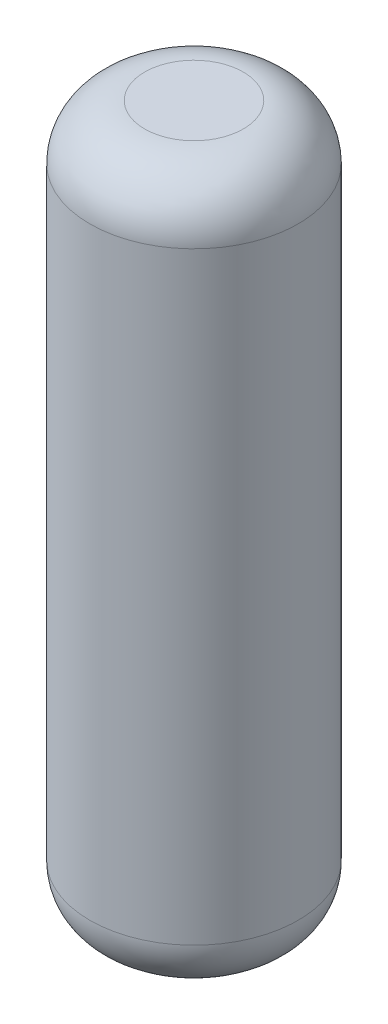
SolidWorks part; units mm, degrees
ref_plane "Front Plane" through (0, 0, 0) normal (0, 0, 1) x (1, 0, 0)
ref_plane "Top Plane" through (0, 0, 0) normal (0, 1, 0) x (1, 0, 0)
ref_plane "Right Plane" through (0, 0, 0) normal (1, 0, 0) x (0, 0, -1)
sketch "Sketch1" plane through (0, 0, 0) normal (0, 1, 0) x (1, 0, 0)
  circle A0 centre (0, 0) radius 48.26
  dimension "D1" = 96.52
extrude "Boss-Extrude1" add sketch "Sketch1" along normal blind 330.2
fillet "Fillet1" radius 25.4 2 edges at (0, 0, 48.26) (0, 330.2, 48.26)
